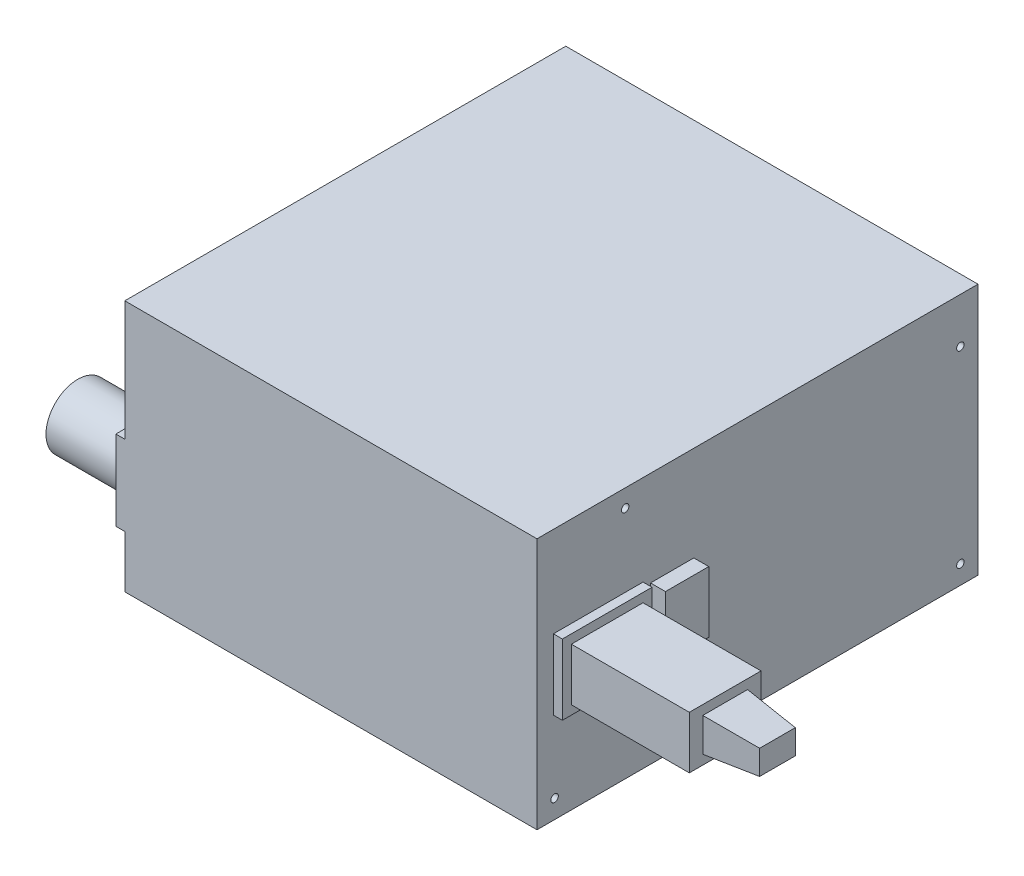
SolidWorks part; units mm, degrees
ref_plane "Front Plane" through (0, 0, 0) normal (0, 0, 1) x (1, 0, 0)
ref_plane "Top Plane" through (0, 0, 0) normal (0, 1, 0) x (1, 0, 0)
ref_plane "Right Plane" through (0, 0, 0) normal (1, 0, 0) x (0, 0, -1)
sketch "Sketch1" plane through (0, 0, 0) normal (0, 1, 0) x (1, 0, 0)
  line L1 (-190.5046, 100.9288) -> (-50.2966, 100.9288)
  line L2 (-190.5046, 100.9288) -> (-190.5046, -49.0712)
  line L3 (-190.5046, -49.0712) -> (-50.2966, -49.0712)
  line L4 (-50.2966, 100.9288) -> (-50.2966, -49.0712)
  line L5 (-190.5046, 100.9288) -> (-50.2966, -49.0712) construction
  line L6 (-190.5046, -49.0712) -> (-50.2966, 100.9288) construction
  point P0 (-120.4006, 25.9288)
  dimension "D1" = 150
  dimension "D2" = 140.208
extrude "Boss-Extrude1" add sketch "Sketch1" along normal blind 85.725
sketch "Sketch2" plane through (-50.2966, 0, 0) normal (1, 0, 0) x (0, 0, -1)
  line L0 (-49.0712, 0) -> (100.9288, 0) construction
  line L1 (-43.4832, 54.9402) -> (-13.0032, 54.9402)
  line L2 (-43.4832, 54.9402) -> (-43.4832, 30.988)
  line L3 (-43.4832, 30.988) -> (-13.0032, 30.988)
  line L4 (-13.0032, 54.9402) -> (-13.0032, 30.988)
  line L5 (-43.4832, 54.9402) -> (-13.0032, 30.988) construction
  line L6 (-43.4832, 30.988) -> (-13.0032, 54.9402) construction
  line L7 (-49.0712, 85.725) -> (-49.0712, 0) construction
  line L9 (-40.4352, 34.036) -> (-16.0512, 34.036)
  line L10 (-40.4352, 34.036) -> (-40.4352, 51.8922)
  line L11 (-40.4352, 51.8922) -> (-16.0512, 51.8922)
  line L12 (-16.0512, 34.036) -> (-16.0512, 51.8922)
  line L13 (-40.4352, 34.036) -> (-16.0512, 51.8922) construction
  line L14 (-40.4352, 51.8922) -> (-16.0512, 34.036) construction
  point P0 (-28.2432, 42.9641)
  point P9 (-28.2432, 42.9641)
  dimension "D1" = 30.48
  dimension "D2" = 23.9522
  dimension "D3" = 30.988
  dimension "D4" = 5.588
  dimension "D5" = 3.048
  dimension "D6" = 3.048
extrude "Boss-Extrude2" add sketch "Sketch2" along normal blind 3.048
sketch "Sketch3" plane through (-50.2966, 0, 0) normal (1, 0, 0) x (0, 0, -1)
  line L0 (-13.0032, 30.988) -> (-13.0032, 54.9402) construction
  line L1 (-10.4632, 53.4162) -> (4.2688, 53.4162)
  line L2 (-10.4632, 53.4162) -> (-10.4632, 32.5882)
  line L3 (-10.4632, 32.5882) -> (4.2688, 32.5882)
  line L4 (4.2688, 53.4162) -> (4.2688, 32.5882)
  line L5 (-10.4632, 53.4162) -> (4.2688, 32.5882) construction
  line L6 (-10.4632, 32.5882) -> (4.2688, 53.4162) construction
  line L7 (-13.0032, 54.9402) -> (-43.4832, 54.9402) construction
  point P0 (-3.0972, 43.0022)
  point P5 (-10.4632, 43.0022)
  dimension "D1" = 20.828
  dimension "D2" = 14.732
  dimension "D3" = 2.54
  dimension "D4" = 1.524
extrude "Boss-Extrude3" add sketch "Sketch3" along normal blind 5.08
sketch "Sketch4" plane through (-50.2966, 0, 0) normal (1, 0, 0) x (0, 0, -1)
  line L0 (94.9288, 85.725) -> (94.9288, 0) construction
  line L1 (-49.0712, 85.725) -> (100.9288, 85.725) construction
  line L2 (-49.0712, 0) -> (100.9288, 0) construction
  line L3 (100.9288, 85.725) -> (100.9288, 0) construction
  line L4 (-49.0712, 6.35) -> (100.9288, 6.35) construction
  line L5 (-49.0712, 85.725) -> (-49.0712, 0) construction
  line L6 (-49.0712, 70.35) -> (100.9288, 70.35) construction
  line L7 (-43.0712, 85.725) -> (-43.0712, 0) construction
  line L8 (100.9288, 79.725) -> (-49.0712, 79.725) construction
  line L9 (-19.0712, 85.725) -> (-19.0712, 0) construction
  circle A0 centre (-43.0712, 6.35) radius 1.27
  circle A1 centre (94.9288, 6.35) radius 1.27
  circle A2 centre (94.9288, 70.35) radius 1.27
  circle A3 centre (-19.0712, 79.725) radius 1.27
  dimension "D1" = 2.54
  dimension "D2" = 6
  dimension "D6" = 2.54
  dimension "D7" = 2.54
  dimension "D10" = 2.54
  dimension "D9" = 114
  dimension "D3" = 6.35
  dimension "D4" = 64
  dimension "D5" = 138
  dimension "D8" = 6
extrude "Cut-Extrude1" cut sketch "Sketch4" against normal blind 3.81
sketch "Sketch5" plane through (-190.5046, 0, 0) normal (-1, 0, 0) x (0, 0, 1)
  line L0 (49.0712, 85.725) -> (49.0712, 0) construction
  line L1 (49.0712, 17.78) -> (26.2112, 17.78)
  line L2 (49.0712, 17.78) -> (49.0712, 44.958)
  line L3 (49.0712, 44.958) -> (26.2112, 44.958)
  line L5 (-100.9288, 0) -> (49.0712, 0) construction
  arc A0 (26.2112, 44.958) -> (26.2112, 17.78) centre (26.2112, 31.369) ccw
  dimension "D1" = 27.178
  dimension "D2" = 22.86
  dimension "D3" = 17.78
extrude "Boss-Extrude4" add sketch "Sketch5" along normal blind 3.048
sketch "Sketch6" plane through (-193.5526, 0, 0) normal (-1, 0, 0) x (0, 0, 1)
  circle A1 centre (36.6227, 31.369) radius 10.795
  dimension "D1" = 21.59
extrude "Boss-Extrude5" add sketch "Sketch6" along normal blind 25.4
sketch "Sketch7" plane through (-50.2966, 0, 0) normal (1, 0, 0) x (0, 0, -1)
  line L1 (-16.0512, 51.8922) -> (-40.4352, 51.8922)
  line L2 (-16.0512, 51.8922) -> (-16.0512, 34.036)
  line L3 (-16.0512, 34.036) -> (-40.4352, 34.036)
  line L4 (-40.4352, 51.8922) -> (-40.4352, 34.036)
extrude "Boss-Extrude6" add sketch "Sketch7" along normal blind 43.18
sketch "Sketch8" plane through (-7.1166, 0, 0) normal (1, 0, 0) x (0, 0, -1)
  line L0 (-16.0512, 42.9641) -> (-40.4352, 42.9641) construction
  line L1 (-16.0512, 34.036) -> (-16.0512, 51.8922) construction
  line L2 (-40.4352, 51.8922) -> (-40.4352, 34.036) construction
  line L4 (-35.8632, 48.6791) -> (-20.6232, 48.6791)
  line L5 (-35.8632, 48.6791) -> (-35.8632, 37.2491)
  line L6 (-35.8632, 37.2491) -> (-20.6232, 37.2491)
  line L7 (-20.6232, 48.6791) -> (-20.6232, 37.2491)
  line L8 (-35.8632, 48.6791) -> (-20.6232, 37.2491) construction
  line L9 (-35.8632, 37.2491) -> (-20.6232, 48.6791) construction
  point P6 (-28.2432, 42.9641)
  dimension "D1" = 11.43
  dimension "D2" = 15.24
extrude "Boss-Extrude7" add sketch "Sketch8" along normal blind 17.78 draft 5
